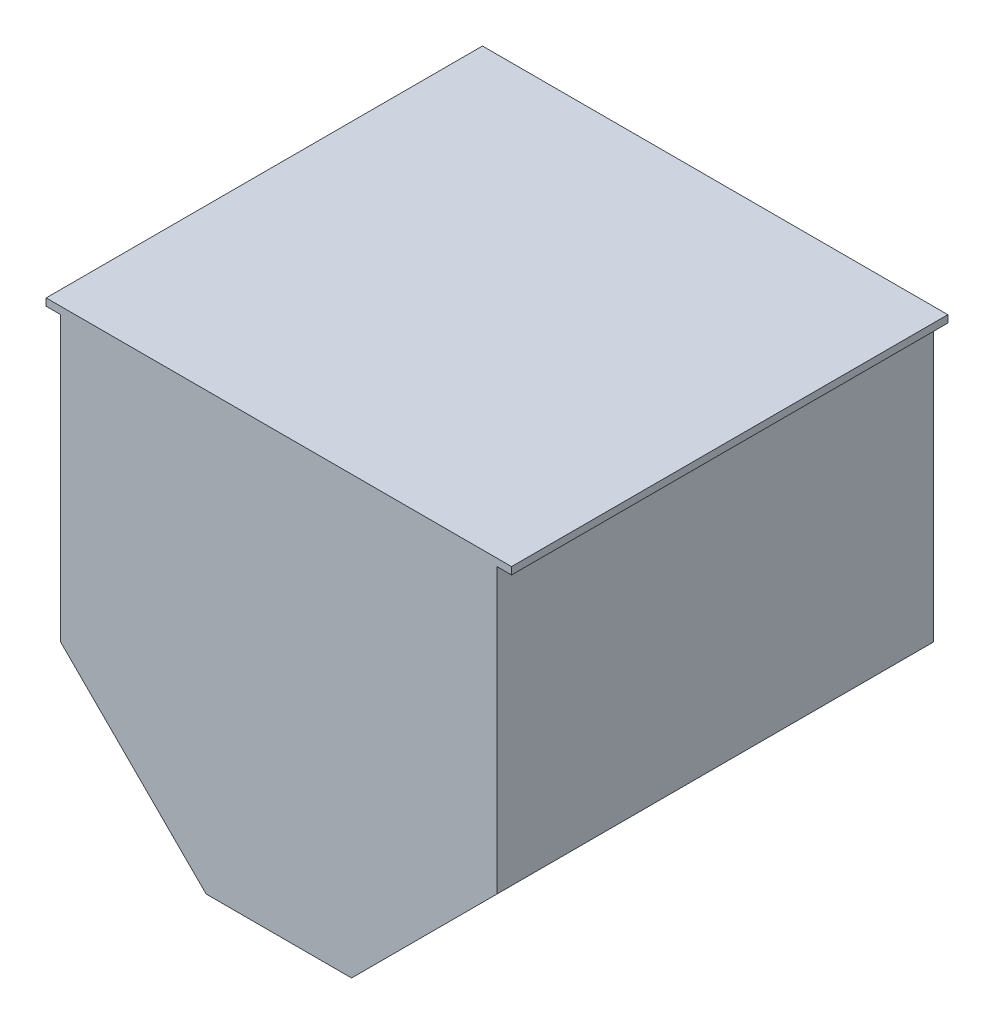
SolidWorks part; units mm, degrees
ref_plane "Front Plane" through (0, 0, 0) normal (0, 0, 1) x (1, 0, 0)
ref_plane "Top Plane" through (0, 0, 0) normal (0, 1, 0) x (1, 0, 0)
ref_plane "Right Plane" through (0, 0, 0) normal (1, 0, 0) x (0, 0, -1)
sketch "Sketch1" plane through (0, 0, 0) normal (0, 0, 1) x (1, 0, 0)
  line L1 (-145.4545, 126.8595) -> (154.5455, 126.8595)
  line L2 (-145.4545, 121.8595) -> (-145.4545, -73.1405)
  line L4 (154.5455, 121.8595) -> (154.5455, -73.1405)
  line L7 (-45.4545, -173.1405) -> (54.5455, -173.1405)
  line L9 (-145.4545, -73.1405) -> (-45.4545, -173.1405)
  line L10 (154.5455, -73.1405) -> (54.5455, -173.1405)
  line L11 (-145.4545, 121.8595) -> (-155.4545, 121.8595)
  line L12 (164.5455, 126.8595) -> (-155.4545, 126.8595)
  line L13 (164.5455, 126.8595) -> (164.5455, 121.8595)
  line L14 (164.5455, 121.8595) -> (154.5455, 121.8595)
  line L15 (-155.4545, 126.8595) -> (-155.4545, 121.8595)
  point P4 (0, 0)
  point P11 (94.3146, 133.9789)
  point P12 (0, 0)
  point P15 (-517.7213, 23.9518)
  point P16 (0, 0)
  point P17 (0, 0)
  point P18 (0, 0)
  point P19 (0, 0)
extrude "Boss-Extrude1" add sketch "Sketch1" along normal blind 300 contours L12 L15 L11 L2 L9 L7 L10 L4 L14 L13 L1
